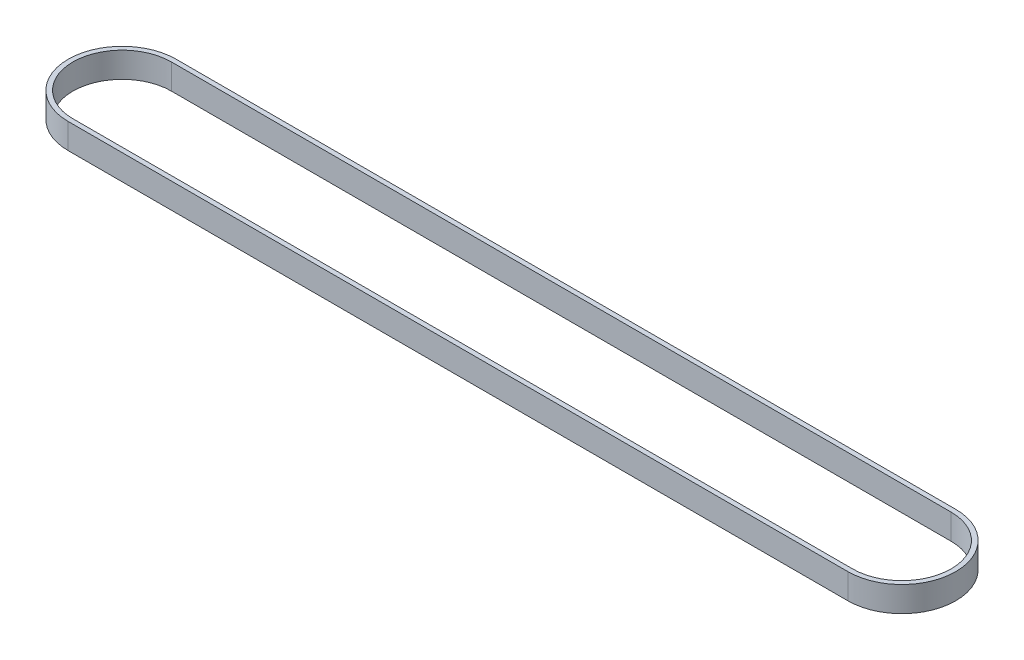
SolidWorks part; units mm, degrees
ref_plane "Front Plane" through (0, 0, 0) normal (0, 0, 1) x (1, 0, 0)
ref_plane "Top Plane" through (0, 0, 0) normal (0, 1, 0) x (1, 0, 0)
ref_plane "Right Plane" through (0, 0, 0) normal (1, 0, 0) x (0, 0, -1)
sketch "Sketch1" plane through (0, 0, 0) normal (0, 1, 0) x (1, 0, 0)
  line L0 (-231.25, 0) -> (231.25, 0) construction
  line L1 (-231.25, 0) -> (231.25, 0) construction
  line L2 (-231.25, 32) -> (231.25, 32)
  line L3 (-231.25, -32) -> (231.25, -32)
  line L4 (-231.25, 0) -> (231.25, 0) construction
  line L5 (-231.25, 29.2) -> (231.25, 29.2)
  line L6 (-231.25, -29.2) -> (231.25, -29.2)
  arc A0 (-231.25, 32) -> (-231.25, -32) centre (-231.25, 0) ccw
  arc A1 (231.25, -32) -> (231.25, 32) centre (231.25, 0) ccw
  arc A2 (-231.25, 29.2) -> (-231.25, -29.2) centre (-231.25, 0) ccw
  arc A3 (231.25, -29.2) -> (231.25, 29.2) centre (231.25, 0) ccw
  point P0 (0, 0)
  point P4 (0, 0)
  point P10 (0, 0)
  dimension "D2" = 32
  dimension "D3" = 29.2
  dimension "D1" = 462.5
extrude "Boss-Extrude1" add sketch "Sketch1" along normal blind 15
